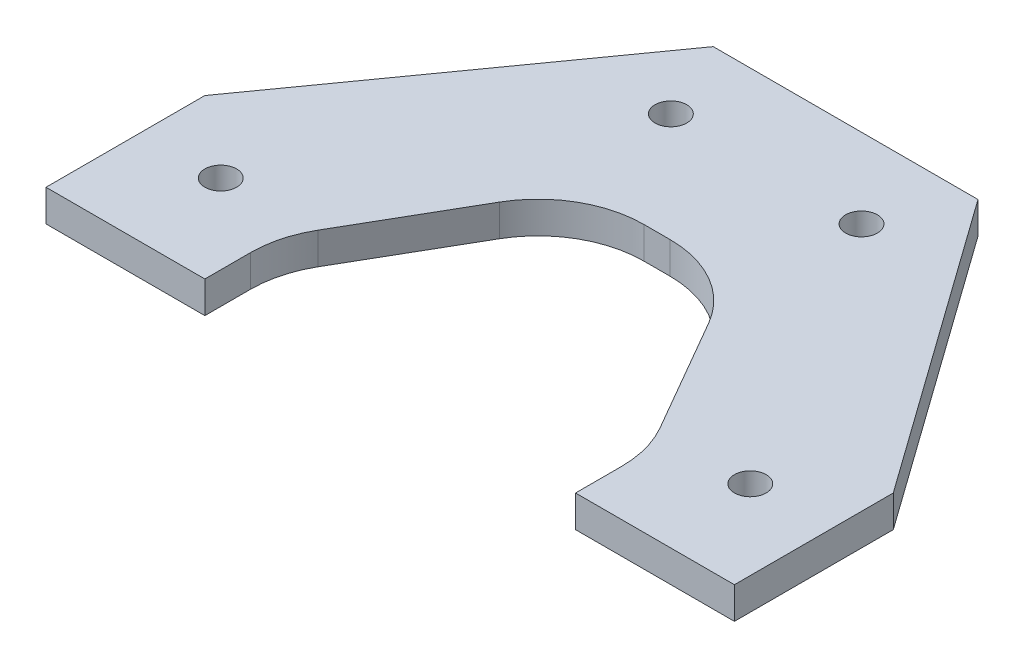
SolidWorks part; units mm, degrees
ref_plane "前视基准面" through (0, 0, 0) normal (0, 0, 1) x (1, 0, 0)
ref_plane "上视基准面" through (0, 0, 0) normal (0, 1, 0) x (1, 0, 0)
ref_plane "右视基准面" through (0, 0, 0) normal (1, 0, 0) x (0, 0, -1)
sketch "草图1" plane through (0, 0, 0) normal (0, 1, 0) x (1, 0, 0)
  line L0 (0, 0) -> (25, 0)
  line L1 (12.5, 0) -> (12.5, -17.8135) construction
  line L2 (13.7265, -17.8135) -> (11.2735, -17.8135)
  line L3 (2.6132, -22.8135) -> (-3.6603, -33.6795)
  line L6 (-20, -28) -> (0, 0)
  line L7 (-5, -38.6795) -> (-5, -43)
  line L8 (-5, -43) -> (-20, -43)
  line L9 (-20, -43) -> (-20, -28)
  line L10 (45, -43) -> (45, -28)
  line L11 (30, -43) -> (45, -43)
  line L12 (30, -38.6795) -> (30, -43)
  line L13 (45, -28) -> (25, 0)
  line L14 (22.3868, -22.8135) -> (28.6603, -33.6795)
  arc A0 (30, -38.6795) -> (28.6603, -33.6795) centre (20, -38.6795) ccw
  arc A1 (-3.6603, -33.6795) -> (-5, -38.6795) centre (5, -38.6795) ccw
  arc A2 (22.3868, -22.8135) -> (13.7265, -17.8135) centre (13.7265, -27.8135) ccw
  arc A3 (11.2735, -17.8135) -> (2.6132, -22.8135) centre (11.2735, -27.8135) ccw
  point P17 (30, -36)
  point P20 (-5, -36)
  point P23 (19.5, -17.8135)
  point P26 (5.5, -17.8135)
  dimension "D9" = 10
  dimension "D1" = 65
  dimension "D2" = 15
  dimension "D3" = 43
  dimension "D4" = 25
  dimension "D5" = 15
  dimension "D6" = 7
  dimension "D7" = 7
  dimension "D8" = 120
extrude "凸台-拉伸1" add sketch "草图1" along normal blind 3
sketch "草图2" plane through (0, 3, 0) normal (0, 1, 0) x (1, 0, 0)
  line L0 (-20, -43) -> (-5, -43) construction
  line L1 (30, -43) -> (45, -43) construction
  line L2 (25, 0) -> (0, 0) construction
  circle A0 centre (-12.5, -34) radius 1.5
  circle A1 centre (37.5, -34) radius 1.5
  circle A2 centre (3.5, -7.5) radius 1.5
  circle A3 centre (21.5, -7.5) radius 1.5
  point P7 (-12.5, -43)
  point P11 (37.5, -43)
  dimension "D2" = 3
  dimension "D3" = 3
  dimension "D4" = 3
  dimension "D5" = 3
  dimension "D1" = 9
  dimension "D6" = 7.5
  dimension "D7" = 7.5
  dimension "D8" = 16
  dimension "D9" = 16
extrude "切除-拉伸1" cut sketch "草图2" against normal blind 3
